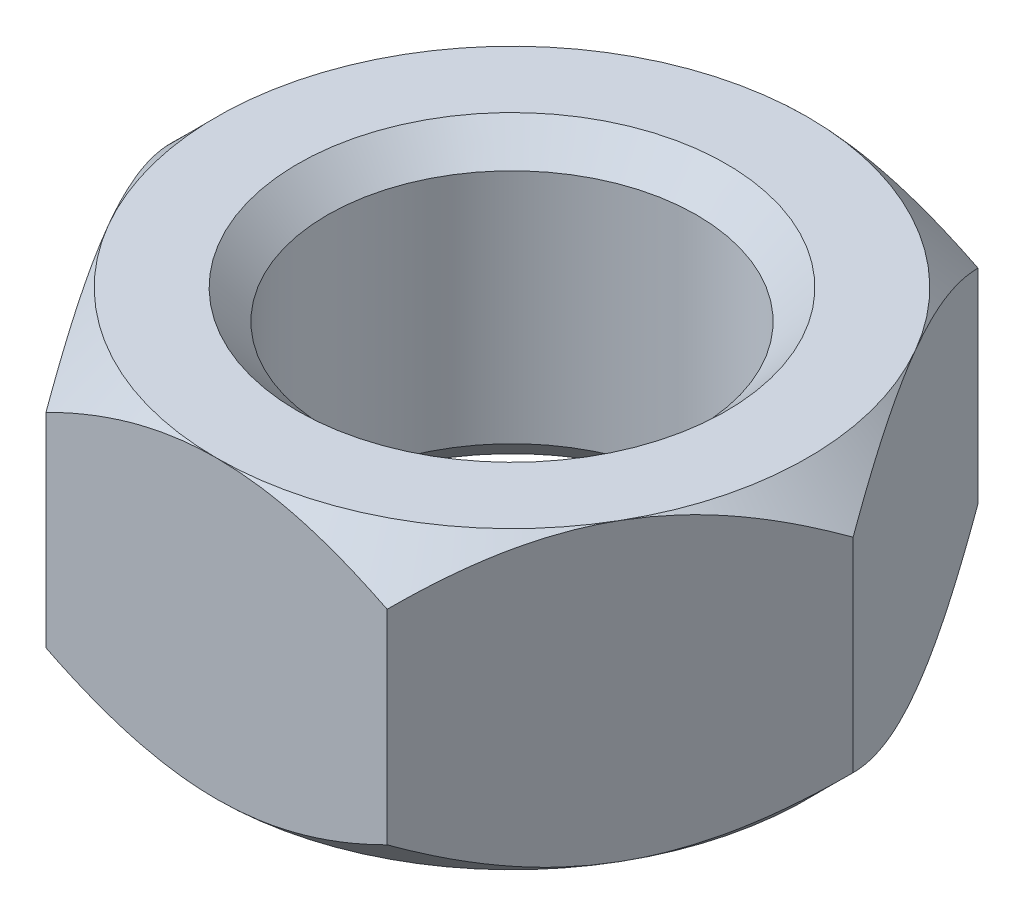
SolidWorks part; units mm, degrees
material "Cast Stainless Steel"
ref_plane "Front Plane" through (0, 0, 0) normal (0, 0, 1) x (1, 0, 0)
ref_plane "Top Plane" through (0, 0, 0) normal (0, 1, 0) x (1, 0, 0)
ref_plane "Right Plane" through (0, 0, 0) normal (1, 0, 0) x (0, 0, -1)
sketch "Sketch1" plane through (0, 0, 0) normal (0, 1, 0) x (1, 0, 0)
  line L0 (-4.6188, 0) -> (4.6188, 0) construction
  line L1 (4.6188, 0) -> (2.3094, 4)
  line L2 (2.3094, 4) -> (-2.3094, 4)
  line L3 (-2.3094, 4) -> (-4.6188, 0)
  line L4 (-4.6188, 0) -> (-2.3094, -4)
  line L5 (-2.3094, -4) -> (2.3094, -4)
  line L6 (2.3094, -4) -> (4.6188, 0)
  circle A0 centre (0, 0) radius 4 construction
  circle A1 centre (0, 0) radius 2.5
  point P12 (0, 0)
  dimension "D1" = 5
  dimension "D2" = 8
extrude "Boss-Extrude1" add sketch "Sketch1" along normal blind 4
sketch "Sketch3" plane through (0, 0, 0) normal (1, 0, 0) x (0, 0, -1)
  line L0 (-4, 0) -> (-5, 1)
  line L1 (-5, 1) -> (-5, 0)
  line L2 (-5, 0) -> (-4, 0)
  line L4 (-4, 2) -> (4, 2) construction
  line L6 (4, 4) -> (4, 0) construction
  line L7 (-5, 4) -> (-4, 4)
  line L8 (-5, 3) -> (-5, 4)
  line L9 (-4, 4) -> (-5, 3)
  line L10 (0, 0) -> (0, 4) construction
  line L12 (-4, 4) -> (-4, 0) construction
  point P7 (0, 2)
  dimension "D1" = 2
  dimension "D2" = 45
  dimension "D3" = 1
revolve "Cut-Revolve1" cut sketch "Sketch3" angle 360 about L10
chamfer "Chamfer1" distance 0.4 angle 45 2 edges at (0, 0, 2.5) (0, 4, 2.5)
equation "\"d\"= 5"
equation "\"m\"= 4"
equation "\"s\"= 8"
equation "\"e\"= 8.79"
equation "\"D1@Sketch1\"=\"d\""
equation "\"D2@Sketch1\"=\"s\""
equation "\"D1@Boss-Extrude1\"=\"m\""
equation "\"D1@Sketch3\"=\"m\"/2"
equation "\"D3@Sketch3\"=\"D1@Sketch3\"-1"
equation "\"D1@Chamfer1\"=\"s\"/20"
